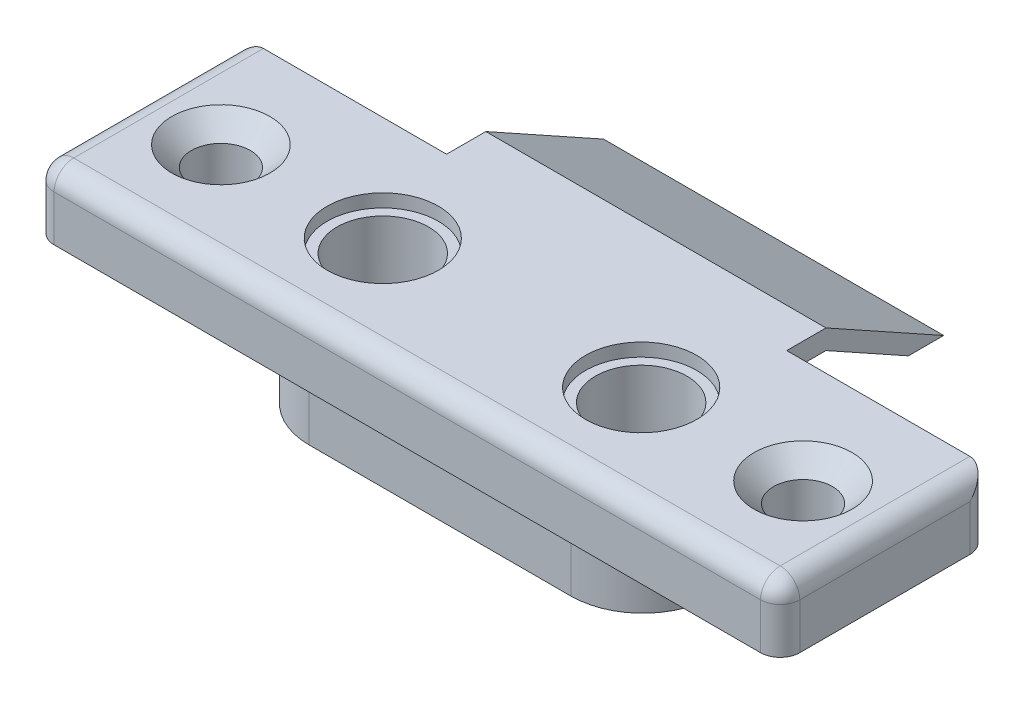
SolidWorks part; units mm, degrees
material "Полипропилен ГОСТ 26996-86"
ref_plane "Спереди" through (0, 0, 0) normal (0, 0, 1) x (1, 0, 0)
ref_plane "Сверху" through (0, 0, 0) normal (0, 1, 0) x (1, 0, 0)
ref_plane "Справа" through (0, 0, 0) normal (1, 0, 0) x (0, 0, -1)
sketch "Эскиз1" plane through (0, 0, 0) normal (0, 1, 0) x (1, 0, 0)
  line L0 (0, 0) -> (0, 16)
  line L1 (0, 16) -> (57, 16)
  line L2 (57, 16) -> (57, 0)
  line L3 (57, 0) -> (0, 0)
  dimension "D1" = 16
  dimension "D2" = 57
extrude "Бобышка-Вытянуть1" add sketch "Эскиз1" along normal blind 5
fillet "Скругление1" radius 1.5 7 edges at (0, 5, -8) (57, 5, -8) (28.5, 5, 0) (0, 2.5, 0) (0, 2.5, -16) (57, 2.5, -16) (57, 2.5, 0)
sketch "Эскиз2" plane through (0, 5, 0) normal (0, 1, 0) x (1, 0, 0)
  line L1 (55.5, 0) -> (1.5, 0) construction
  line L2 (0, 1.5) -> (0, 14.5) construction
  line L3 (57, 14.5) -> (57, 1.5) construction
  circle A2 centre (18.625, 8) radius 4.25
  circle A3 centre (38.375, 8) radius 4.25
  dimension "D1" = 8
  dimension "D2" = 18.625
  dimension "D4" = 8
  dimension "D5" = 18.625
  dimension "D6" = 8.5
  dimension "D7" = 8.5
hole_wizard "Отверстие с зазором M41" positions "Эскиз5" profile "Эскиз6" hole size "M4" standard "ISO" end condition through all
sketch "Эскиз5" plane through (0, 5, 0) normal (0, 1, 0) x (1, 0, 0)
  line L0 (28.5, 14.5) -> (28.5, 1.5) construction
  line L2 (1.5, 1.5) -> (55.5, 1.5) construction
  point P0 (6.25, 8)
  point P3 (50.75, 8)
  dimension "D1" = 44.5
  dimension "D2" = 22.25
  dimension "D3" = 6.5
  dimension "D4" = 6.5
sketch "Эскиз6" plane through (6.25, 5, -8) normal (1, 0, 0) x (0, 0, 1)
  line L0 (0, 0) -> (0, 5)
  line L1 (0, 5) -> (2.25, 5)
  line L2 (2.25, 5) -> (2.25, 0)
  line L5 (2.25, 0) -> (0, 0)
  line L11 (0, -6.35) -> (0, 107.95) construction
  dimension "Диаметр сквозного отверстия" = 4.5
  dimension "Глубина сквозного отверстия" = 5
chamfer "Фаска1" distance 1.5 angle 45 2 edges at (50.75, 5, -5.75) (6.25, 5, -5.75)
extrude "Вырез-Вытянуть1" cut sketch "Эскиз2" against normal blind 1
sketch "Эскиз7" plane through (0, 4, 0) normal (0, 1, 0) x (1, 0, 0)
  circle A0 centre (18.625, 8) radius 3.5
  circle A1 centre (38.375, 8) radius 3.5
  dimension "D1" = 7
  dimension "D2" = 7
extrude "Вырез-Вытянуть2" cut sketch "Эскиз7" against normal through all
ref_plane "Плоскость1" through (28.5, 0, 0) normal (-1, 0, 0) x (0, 0, 1)
sketch "Эскиз9" plane through (28.5, 0, 0) normal (-1, 0, 0) x (0, 0, 1)
  line L0 (-19, 5) -> (-28, 0)
  line L1 (-19, 3.5) -> (-25.3, 0)
  line L2 (-16, 5) -> (-19, 5)
  line L3 (-16, 5) -> (-16, 3.5)
  line L4 (-16, 0) -> (-16, 5) construction
  line L5 (-16, 3.5) -> (-19, 3.5)
  line L6 (-25.3, 0) -> (-28, 0)
extrude "Бобышка-Вытянуть2" add sketch "Эскиз9" along normal blind 13 and the other way blind 13
sketch "Эскиз10" plane through (0, 0, 0) normal (0, -1, 0) x (1, 0, 0)
  line L0 (18.5, -13.5) -> (38.5, -13.5)
  line L1 (38.5, -2.5) -> (18.5, -2.5)
  line L3 (1.5, 0) -> (55.5, 0) construction
  line L4 (57, -1.5) -> (57, -14.5) construction
  arc A0 (18.5, -2.5) -> (18.5, -13.5) centre (18.5, -8) ccw
  arc A1 (38.5, -13.5) -> (38.5, -2.5) centre (38.5, -8) ccw
  circle A2 centre (38.375, -8) radius 3.5
  circle A3 centre (18.625, -8) radius 3.5 construction
  circle A4 centre (18.625, -8) radius 3.5
  dimension "D1" = 20
  dimension "D3" = 5.5
  dimension "D4" = 5.5
  dimension "D2" = 11
  dimension "D5" = 2.5
  dimension "D6" = 18.5
extrude "Бобышка-Вытянуть3" add sketch "Эскиз10" along normal blind 6
sketch "Эскиз11" plane through (0, -6, 0) normal (0, -1, 0) x (1, 0, 0)
  circle A0 centre (28.5, -8) radius 2.25
  dimension "D1" = 4.5
extrude "Вырез-Вытянуть3" cut sketch "Эскиз11" against normal blind 9.25
sketch "Эскиз12" plane through (0, -6, 0) normal (0, -1, 0) x (1, 0, 0)
  circle A0 centre (28.5, -8) radius 4
  circle A1 centre (28.5, -8) radius 2.25
  dimension "D1" = 8
  dimension "D2" = 4.5
extrude "Бобышка-Вытянуть4" add sketch "Эскиз12" along normal blind 0.1
sketch "Эскиз13" plane through (0, 0, -13.5) normal (0, 0, -1) x (-1, 0, 0)
  line L2 (-18.5, -6) -> (-38.5, -6) construction
  line L3 (-18.5, -6) -> (-18.5, 0) construction
  line L4 (-38.5, -6) -> (-38.5, 0) construction
  circle A0 centre (-38.375, -3) radius 1.75
  circle A1 centre (-18.625, -3) radius 1.75
  dimension "D1" = 3.5
  dimension "D2" = 3.5
  dimension "D3" = 3
  dimension "D4" = 0.125
  dimension "D5" = 3
  dimension "D6" = 0.125
extrude "Вырез-Вытянуть4" cut sketch "Эскиз13" against normal blind 5
